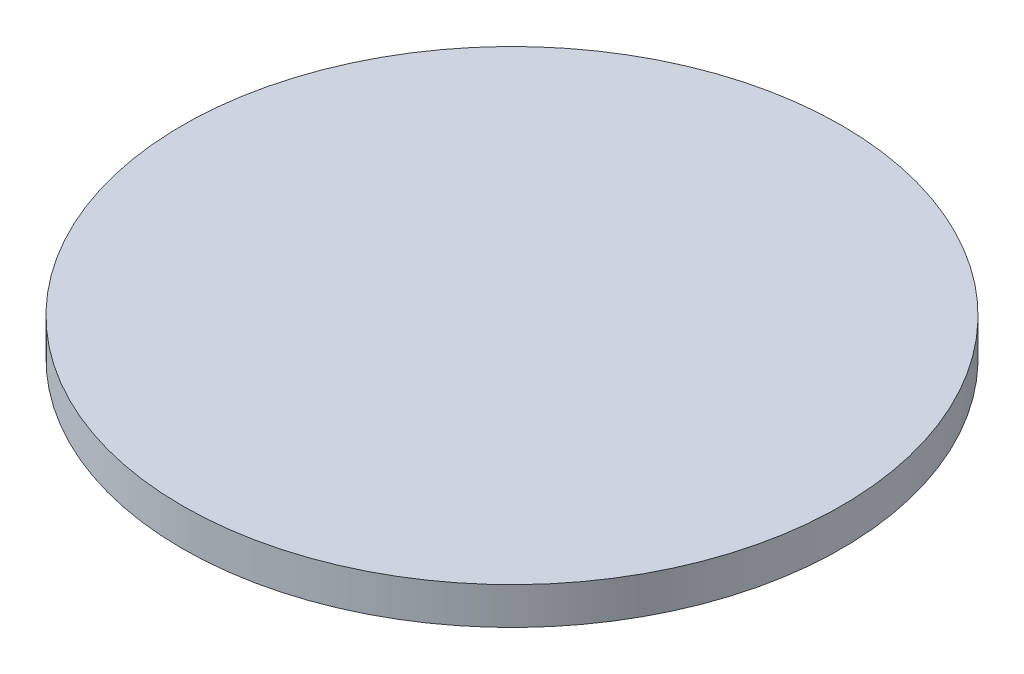
SolidWorks part; units mm, degrees
material "6061-T6 (SS)"
ref_plane "Front Plane" through (0, 0, 0) normal (0, 0, 1) x (1, 0, 0)
ref_plane "Top Plane" through (0, 0, 0) normal (0, 1, 0) x (1, 0, 0)
ref_plane "Right Plane" through (0, 0, 0) normal (1, 0, 0) x (0, 0, -1)
sketch "Sketch1" plane through (0, 0, 0) normal (0, 1, 0) x (1, 0, 0)
  circle A0 centre (0, 0) radius 85.725
  dimension "D1" = 171.45
extrude "Boss-Extrude1" add sketch "Sketch1" along normal mid plane 9.652
sketch "Sketch2" plane through (0, -4.826, 0) normal (0, -1, 0) x (1, 0, 0)
  circle A0 centre (0, 0) radius 19.05
  dimension "D1" = 38.1
extrude "Cut-Extrude1" [suppressed] cut sketch "Sketch2" against normal up to surface (9.652 mm away)
ref_plane "Plane1" through (-85.725, 0, 0) normal (-1, 0, 0) x (0, 0, 1)
sketch "Sketch3" plane through (-85.725, 0, 0) normal (-1, 0, 0) x (0, 0, 1)
  circle A0 centre (0, 0) radius 1.6637
  dimension "D1" = 3.3274
extrude "Cut-Extrude2" [suppressed] cut sketch "Sketch3" against normal blind 15.24
pattern_circular "CirPattern1" [suppressed] count 3 over 360
